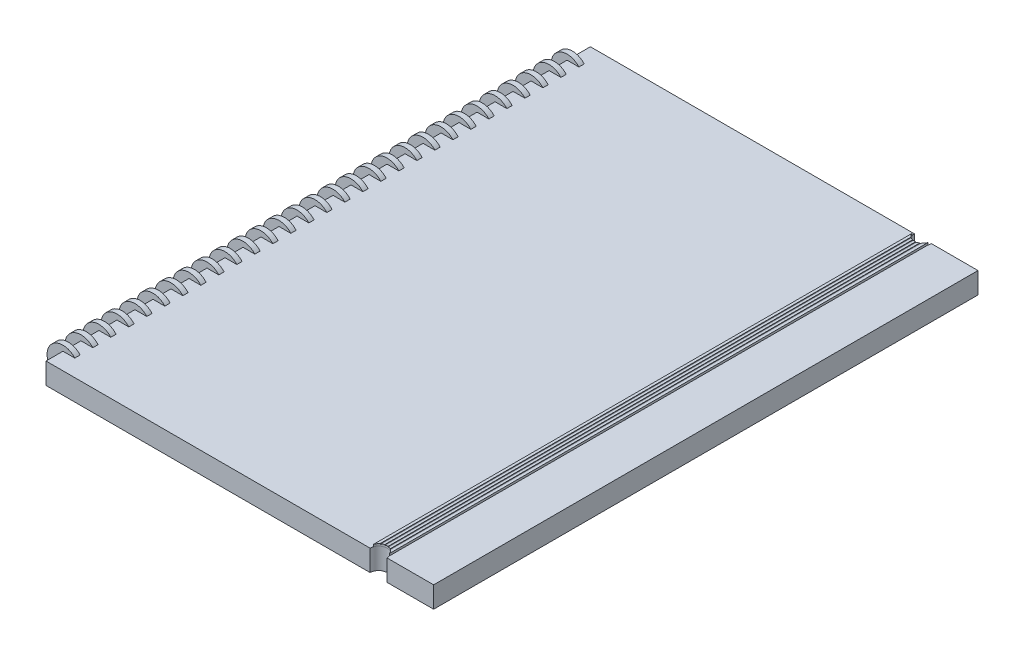
SolidWorks part; units mm, degrees
ref_plane "정면" through (0, 0, 0) normal (0, 0, 1) x (1, 0, 0)
ref_plane "윗면" through (0, 0, 0) normal (0, 1, 0) x (1, 0, 0)
ref_plane "우측면" through (0, 0, 0) normal (1, 0, 0) x (0, 0, -1)
sketch "스케치1" plane through (0, 0, 0) normal (0, 1, 0) x (1, 0, 0)
  line L1 (-91.5, -128.5) -> (91.5, -128.5)
  line L2 (-91.5, -128.5) -> (-91.5, 128.5)
  line L3 (-91.5, 128.5) -> (91.5, 128.5)
  line L4 (91.5, -128.5) -> (91.5, 128.5)
  line L5 (-91.5, -128.5) -> (91.5, 128.5) construction
  line L6 (-91.5, 128.5) -> (91.5, -128.5) construction
  point P0 (0, 0)
  dimension "D1" = 183
  dimension "D2" = 257
extrude "보스-돌출1" add sketch "스케치1" along normal blind 10
sketch "스케치2" plane through (0, 0, 128.5) normal (0, 0, 1) x (1, 0, 0)
  line L7 (-91.5, 10) -> (-91.5, 0) construction
  circle A0 centre (-91.5, 5) radius 7.5
extrude "보스-돌출2" add sketch "스케치2" against normal blind 2.5 from offset 8 offset against normal yes
pattern_linear "선형 패턴1" count 29 spacing 8.5 along (0, 0, -1) of "보스-돌출2"
sketch "스케치3" plane through (0, 10, 0) normal (0, 1, 0) x (1, 0, 0)
  line L0 (65.5, 128.5) -> (65.5, -128.5) construction
  line L1 (91.5, 128.5) -> (-91.5, 128.5) construction
  line L2 (-91.5, -128.5) -> (91.5, -128.5) construction
  line L3 (91.5, -128.5) -> (91.5, 128.5) construction
  line L5 (61.75, 128.5) -> (69.25, 128.5)
  line L6 (61.75, 128.5) -> (61.75, -128.5)
  line L7 (61.75, -128.5) -> (69.25, -128.5)
  line L8 (69.25, 128.5) -> (69.25, -128.5)
  line L9 (61.75, 128.5) -> (69.25, -128.5) construction
  line L10 (61.75, -128.5) -> (69.25, 128.5) construction
  point P8 (65.5, 0)
  dimension "D1" = 26
  dimension "D2" = 7.5
extrude "보스-돌출3" add sketch "스케치3" along normal blind 1 separate body
sketch "스케치4" plane through (0, 0, 128.5) normal (0, 0, 1) x (1, 0, 0)
  line L0 (61.75, 11) -> (69.25, 11) construction
  line L1 (63, 11.2) -> (63.5, 11.2)
  line L2 (63, 11.2) -> (63, 10.8)
  line L3 (63, 10.8) -> (63.5, 10.8)
  line L4 (63.5, 11.2) -> (63.5, 10.8)
  line L5 (63, 11.2) -> (63.5, 10.8) construction
  line L6 (63, 10.8) -> (63.5, 11.2) construction
  line L7 (61.75, 11) -> (61.75, 10) construction
  line L8 (64.5, 11.2) -> (64.5, 10.8)
  line L9 (64.5, 11.2) -> (65, 11.2)
  line L10 (65, 11.2) -> (65, 10.8)
  line L11 (64.5, 10.8) -> (65, 10.8)
  line L12 (66, 11.2) -> (66, 10.8)
  line L13 (66, 11.2) -> (66.5, 11.2)
  line L14 (66.5, 11.2) -> (66.5, 10.8)
  line L15 (66, 10.8) -> (66.5, 10.8)
  line L16 (67.5, 11.2) -> (67.5, 10.8)
  line L17 (67.5, 11.2) -> (68, 11.2)
  line L18 (68, 11.2) -> (68, 10.8)
  line L19 (67.5, 10.8) -> (68, 10.8)
  point P0 (63.25, 11)
  dimension "D1" = 1.5
  dimension "D2" = 4
  dimension "D3" = 0.5
  dimension "D4" = 0.4
extrude "컷-돌출1" cut sketch "스케치4" against normal up to next (257 mm away)
sketch "스케치5" plane through (0, 10, 0) normal (0, 1, 0) x (1, 0, 0)
  line L0 (66, 128.5) -> (65, 128.5) construction
  circle A0 centre (65.5, 128.5) radius 4
extrude "컷-돌출2" cut sketch "스케치5" against normal blind 50 and the other way blind 50
sketch "스케치6" plane through (0, 11, 0) normal (0, 1, 0) x (1, 0, 0)
  line L0 (66, 128.5) -> (65, 128.5) construction
  circle A0 centre (65.5, 128.5) radius 4
extrude "컷-돌출3" cut sketch "스케치6" against normal blind 1
sketch "스케치7" plane through (0, 11, 0) normal (0, 1, 0) x (1, 0, 0)
  line L0 (65, -128.5) -> (66, -128.5) construction
  circle A0 centre (65.5, -128.5) radius 4
extrude "컷-돌출4" cut sketch "스케치7" against normal blind 50
